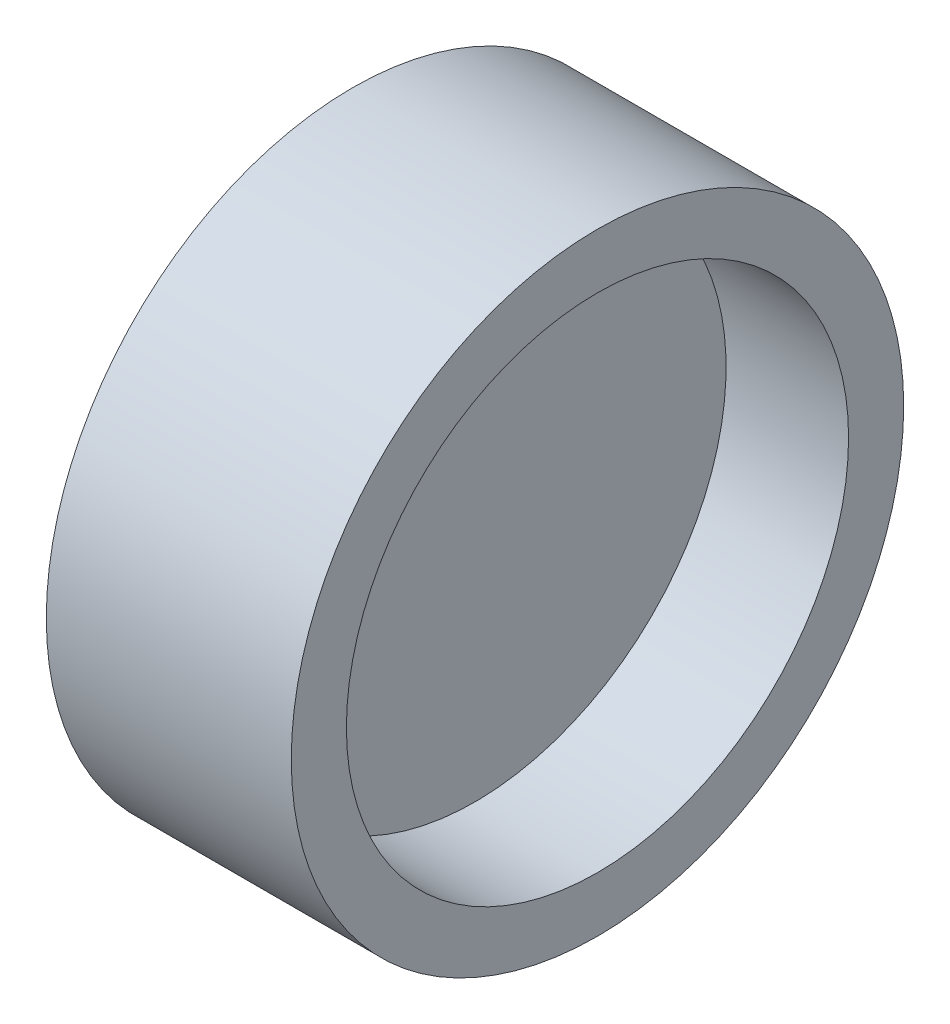
SolidWorks part; units mm, degrees
ref_plane "Front Plane" through (0, 0, 0) normal (0, 0, 1) x (1, 0, 0)
ref_plane "Top Plane" through (0, 0, 0) normal (0, 1, 0) x (1, 0, 0)
ref_plane "Right Plane" through (0, 0, 0) normal (1, 0, 0) x (0, 0, -1)
sketch "Sketch1" plane through (0, 0, 0) normal (1, 0, 0) x (0, 0, -1)
  circle A0 centre (0, 0) radius 4.1
  circle A1 centre (0, 0) radius 5
  dimension "D1" = 8.2
  dimension "D2" = 10
extrude "Boss-Extrude1" add sketch "Sketch1" along normal blind 4
sketch "Sketch2" plane through (0, 0, 0) normal (-1, 0, 0) x (0, 0, 1)
  circle A0 centre (0, 0) radius 4.1
  circle A1 centre (0, 0) radius 2.1
  dimension "D1" = 4.2
extrude "Boss-Extrude2" add sketch "Sketch2" against normal blind 2
sketch "Sketch3" plane through (2, 0, 0) normal (1, 0, 0) x (0, 0, -1)
  circle A0 centre (0, 0) radius 2.1
extrude "Boss-Extrude3" add sketch "Sketch3" against normal blind 0.5
